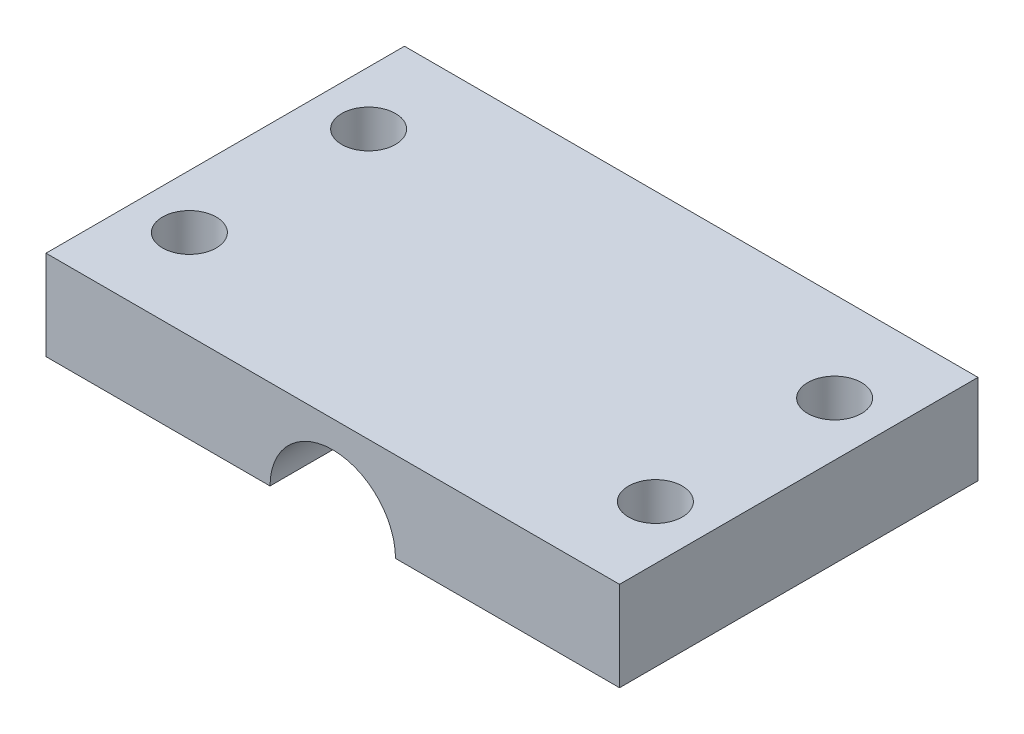
SolidWorks part; units mm, degrees
ref_plane "Front Plane" through (0, 0, 0) normal (0, 0, 1) x (1, 0, 0)
ref_plane "Top Plane" through (0, 0, 0) normal (0, 1, 0) x (1, 0, 0)
ref_plane "Right Plane" through (0, 0, 0) normal (1, 0, 0) x (0, 0, -1)
sketch "Sketch1" plane through (0, 0, 0) normal (0, 0, 1) x (1, 0, 0)
  line L5 (8.1352, -2.1805) -> (-4.3648, -2.1805)
  line L6 (-4.3648, -2.1805) -> (-4.3648, 2.8195)
  line L7 (-4.3648, 2.8195) -> (27.6352, 2.8195)
  line L8 (27.6352, 2.8195) -> (27.6352, -2.1805)
  line L9 (27.6352, -2.1805) -> (15.1352, -2.1805)
  arc A1 (8.1352, -2.1805) -> (15.1352, -2.1805) centre (11.6352, -2.1805) cw
  dimension "D1" = 12.5
  dimension "D2" = 12.5
  dimension "D3" = 7
  dimension "D4" = 5
extrude "Boss-Extrude1" add sketch "Sketch1" along normal blind 20
sketch "Sketch3" plane through (0, -2.1805, 0) normal (0, -1, 0) x (1, 0, 0)
  line L0 (-4.3648, 20) -> (-4.3648, 0) construction
  line L1 (-4.3648, 0) -> (8.1352, 0) construction
  line L2 (27.6352, 20) -> (27.6352, 0) construction
  line L3 (15.1352, 0) -> (27.6352, 0) construction
  circle A0 centre (-1.3648, 15) radius 1.5
  circle A1 centre (-1.3648, 5) radius 1.5
  circle A2 centre (24.6352, 15) radius 1.5
  circle A3 centre (24.6352, 5) radius 1.5
  point P8 (0, 0)
  point P13 (24.3536, 16.3592)
  point P18 (0, 0)
  dimension "D1" = 3
  dimension "D2" = 3
  dimension "D3" = 3
  dimension "D4" = 5
  dimension "D5" = 10
  dimension "D6" = 3
  dimension "D7" = 10
  dimension "D8" = 5
extrude "Cut-Extrude1" cut sketch "Sketch3" against normal up to next
